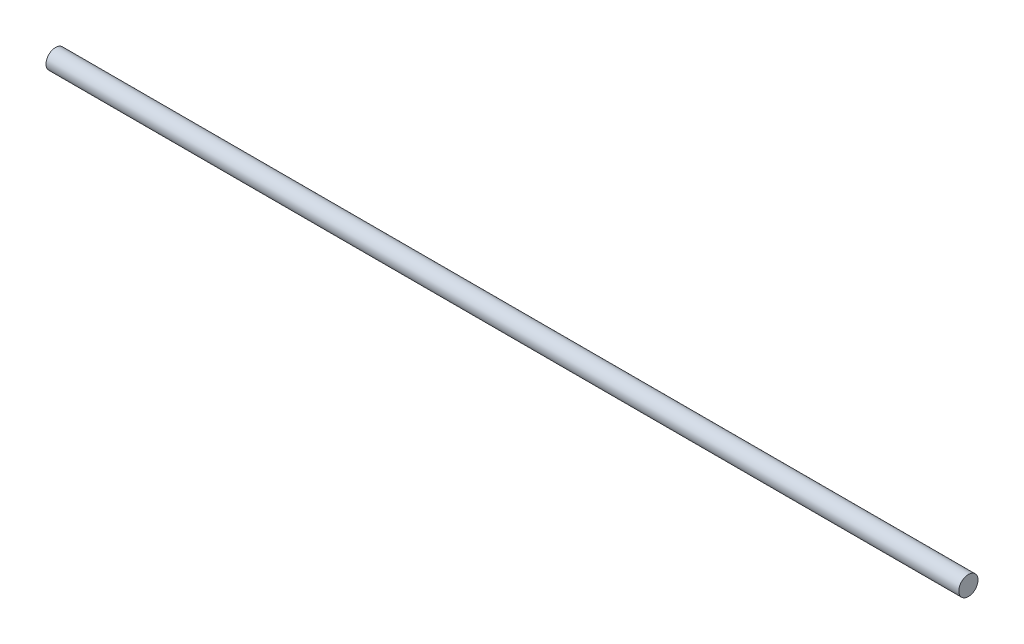
SolidWorks part; units mm, degrees
ref_plane "Front Plane" through (0, 0, 0) normal (0, 0, 1) x (1, 0, 0)
ref_plane "Top Plane" through (0, 0, 0) normal (0, 1, 0) x (1, 0, 0)
ref_plane "Right Plane" through (0, 0, 0) normal (1, 0, 0) x (0, 0, -1)
sketch "Sketch1" plane through (0, 0, 0) normal (1, 0, 0) x (0, 0, -1)
  circle A0 centre (0, 0) radius 12.7
  dimension "D1" = 25.4
extrude "Boss-Extrude1" add sketch "Sketch1" along normal blind 1206.5
